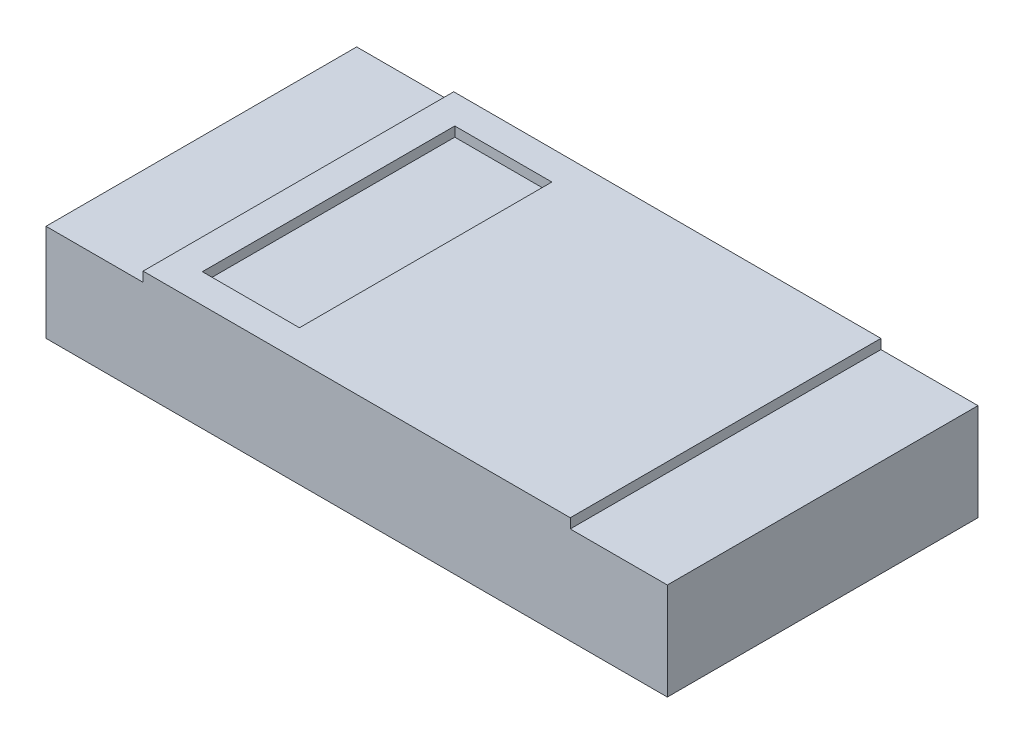
SolidWorks part; units mm, degrees
ref_plane "Front Plane" through (0, 0, 0) normal (0, 0, 1) x (1, 0, 0)
ref_plane "Top Plane" through (0, 0, 0) normal (0, 1, 0) x (1, 0, 0)
ref_plane "Right Plane" through (0, 0, 0) normal (1, 0, 0) x (0, 0, -1)
sketch "Sketch1" plane through (0, 0, 0) normal (0, 1, 0) x (1, 0, 0)
  line L1 (-1.6, -0.8) -> (1.6, -0.8)
  line L2 (-1.6, -0.8) -> (-1.6, 0.8)
  line L3 (-1.6, 0.8) -> (1.6, 0.8)
  line L4 (1.6, -0.8) -> (1.6, 0.8)
  line L5 (-1.6, -0.8) -> (1.6, 0.8) construction
  line L6 (-1.6, 0.8) -> (1.6, -0.8) construction
  point P0 (0, 0)
  dimension "D1" = 1.6
  dimension "D2" = 3.2
extrude "Boss-Extrude1" add sketch "Sketch1" along normal blind 0.5
sketch "Sketch2" plane through (0, 0.5, 0) normal (0, 1, 0) x (1, 0, 0)
  line L0 (1.6, 0.8) -> (-1.6, 0.8) construction
  line L1 (-1.1, 0.8) -> (1.1, 0.8)
  line L2 (-1.1, 0.8) -> (-1.1, -0.8)
  line L3 (-1.1, -0.8) -> (1.1, -0.8)
  line L4 (1.1, 0.8) -> (1.1, -0.8)
  line L5 (-1.6, -0.8) -> (1.6, -0.8) construction
  point P8 (0, 0.8)
  point P9 (0, 0.8)
  dimension "D1" = 2.2
extrude "Boss-Extrude2" add sketch "Sketch2" along normal blind 0.05
sketch "Sketch3" plane through (0, 0.55, 0) normal (0, 1, 0) x (1, 0, 0)
  line L0 (-1.1, 0.8) -> (-1.1, -0.8) construction
  line L1 (-0.9447, 0.65) -> (-0.4447, 0.65)
  line L2 (-0.9447, 0.65) -> (-0.9447, -0.65)
  line L3 (-0.9447, -0.65) -> (-0.4447, -0.65)
  line L4 (-0.4447, 0.65) -> (-0.4447, -0.65)
  point P6 (-1.1, 0)
  point P7 (-0.9447, 0)
  dimension "D1" = 0.5
  dimension "D2" = 1.3
extrude "Cut-Extrude1" cut sketch "Sketch3" against normal blind 0.05
